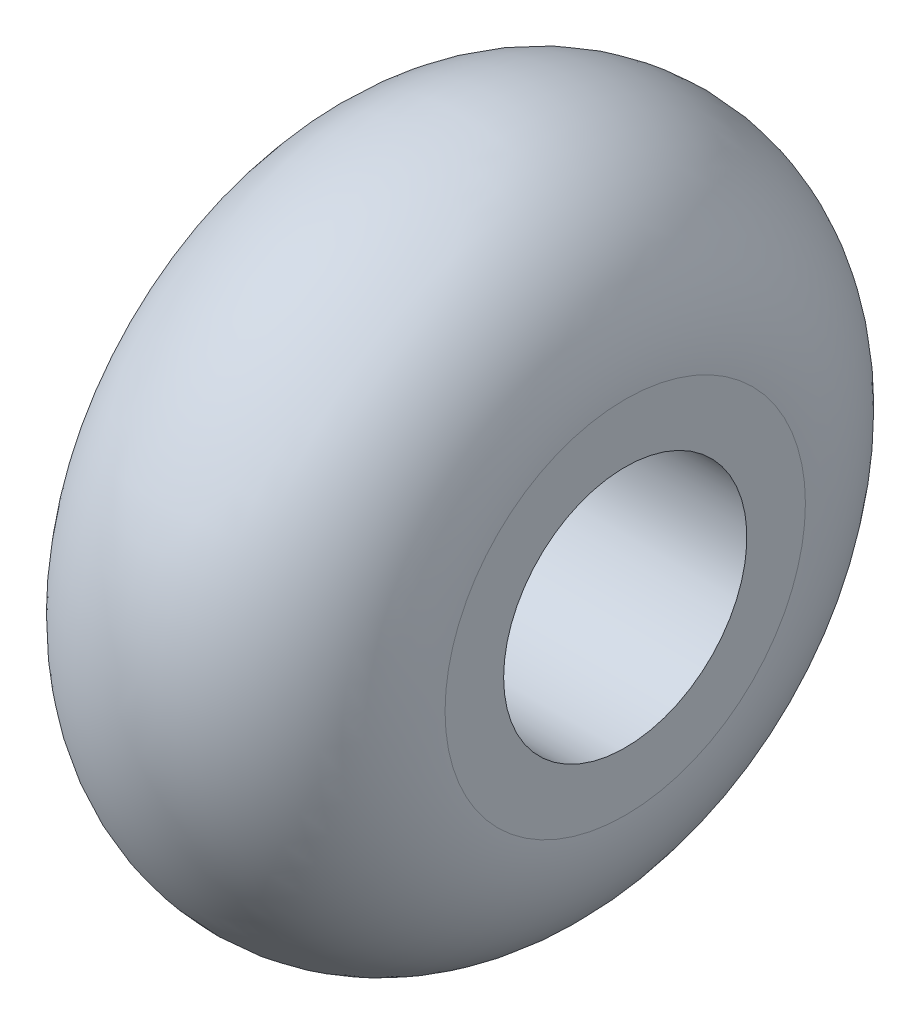
SolidWorks part; units mm, degrees
ref_plane "Płaszczyzna przednia" through (0, 0, 0) normal (0, 0, 1) x (1, 0, 0)
ref_plane "Płaszczyzna górna" through (0, 0, 0) normal (0, 1, 0) x (1, 0, 0)
ref_plane "Płaszczyzna prawa" through (0, 0, 0) normal (1, 0, 0) x (0, 0, -1)
sketch "Sketch1" plane through (0, 0, 0) normal (0, 0, 1) x (1, 0, 0)
  line L0 (0, 11.6871) -> (0, 0) construction
  line L1 (0, 0) -> (16.5, 0) construction
  line L2 (0, 4.05) -> (11, 4.05)
  line L3 (11, 4.05) -> (11, 6)
  line L4 (0, 4.05) -> (0, 6)
  arc A0 (0, 6) -> (11, 6) centre (5.5, 6) cw
  point P9 (0, 0)
  dimension "D4" = 5.5
  dimension "D1" = 4.05
  dimension "D2" = 6
  dimension "D3" = 11
revolve "Revolve1" add sketch "Sketch1" angle 360 about L1
